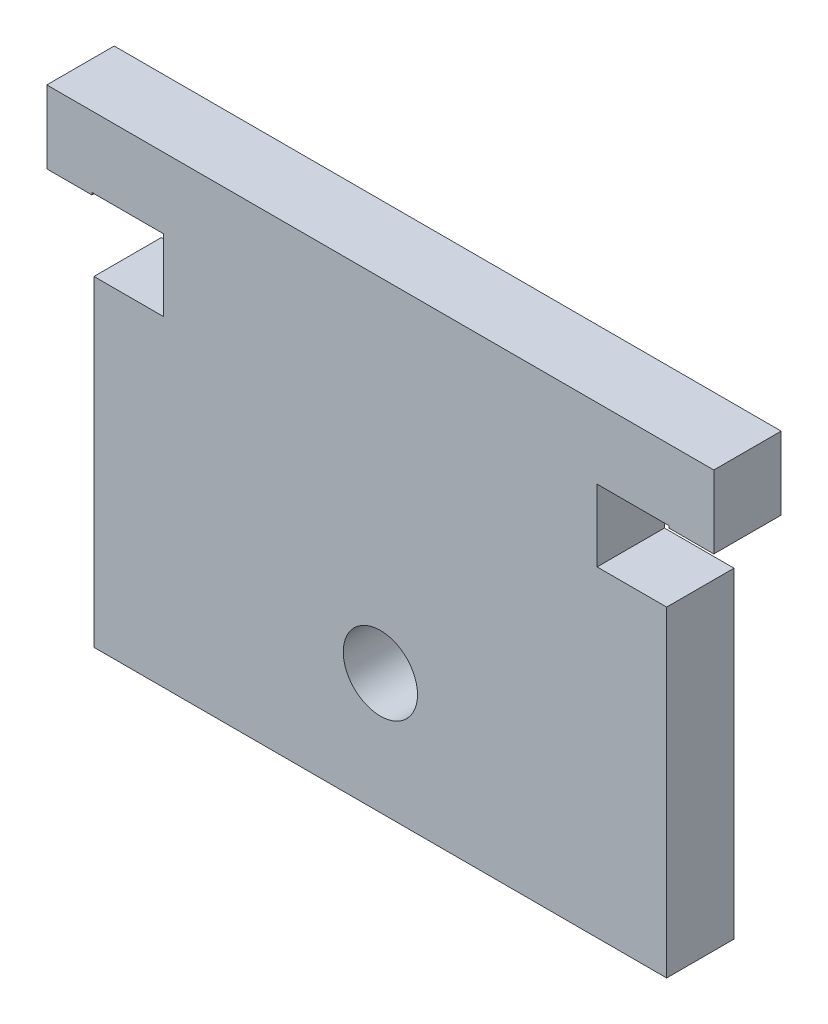
SolidWorks part; units mm, degrees
material "AISI 4130 Steel, annealed at 865C"
ref_plane "X-Y Datum" through (0, 0, 0) normal (0, 0, 1) x (1, 0, 0)
ref_plane "X-Z Datum" through (0, 0, 0) normal (0, 1, 0) x (1, 0, 0)
ref_plane "Y-Z Datum" through (0, 0, 0) normal (1, 0, 0) x (0, 0, -1)
sketch "Sketch1" plane through (0, 0, 0) normal (0, 0, 1) x (1, 0, 0)
  line L1 (-42.8625, -25.4) -> (42.8625, -25.4)
  line L2 (-42.8625, -25.4) -> (-42.8625, 25.4)
  line L3 (-42.8625, 25.4) -> (42.8625, 25.4)
  line L4 (42.8625, -25.4) -> (42.8625, 25.4)
  line L5 (-42.8625, -25.4) -> (42.8625, 25.4) construction
  line L6 (-42.8625, 25.4) -> (42.8625, -25.4) construction
  point P0 (0, 0)
  dimension "D1" = 85.725
  dimension "D2" = 50.8
extrude "Boss-Extrude1" add sketch "Sketch1" along normal blind 6.35
sketch "Sketch2" plane through (0, 0, 6.35) normal (0, 0, 1) x (1, 0, 0)
  line L1 (-42.8625, -25.4) -> (-26.9875, -25.4)
  line L2 (-42.8625, -25.4) -> (-42.8625, 17.78)
  line L3 (-42.8625, 17.78) -> (-26.9875, 17.78)
  line L4 (-26.9875, -25.4) -> (-26.9875, 17.78)
  line L5 (42.8625, -25.4) -> (26.9875, -25.4)
  line L6 (42.8625, -25.4) -> (42.8625, 17.78)
  line L7 (42.8625, 17.78) -> (26.9875, 17.78)
  line L8 (26.9875, -25.4) -> (26.9875, 17.78)
  dimension "D1" = 15.875
  dimension "D2" = 43.18
extrude "Cut-Extrude1" cut sketch "Sketch2" against normal blind 6.35
sketch "Sketch3" plane through (0, 25.4, 0) normal (0, 1, 0) x (1, 0, 0)
  line L1 (-42.8625, 0) -> (42.8625, 0)
  line L2 (-42.8625, 0) -> (-42.8625, -6.35)
  line L3 (-42.8625, -6.35) -> (42.8625, -6.35)
  line L4 (42.8625, 0) -> (42.8625, -6.35)
extrude "Cut-Extrude2" cut sketch "Sketch3" against normal blind 0.762
sketch "Sketch5" plane through (-26.9875, 0, 0) normal (-1, 0, 0) x (0, 0, 1)
  line L0 (6.35, -25.4) -> (6.35, 17.78) construction
  line L1 (0, 17.78) -> (6.35, 17.78)
  line L2 (0, 17.78) -> (0, 11.43)
  line L3 (0, 11.43) -> (6.35, 11.43)
  line L4 (6.35, 17.78) -> (6.35, 11.43)
  dimension "D1" = 6.35
extrude "Cut-Extrude3" cut sketch "Sketch5" against normal blind 6.35
mirror "Mirror1" about plane through (0, 0, 0) normal (1, 0, 0) of "Cut-Extrude3"
sketch "Sketch6" plane through (0, 0, 6.35) normal (0, 0, 1) x (1, 0, 0)
  line L12 (26.9875, 11.43) -> (20.6375, 11.43)
  line L13 (20.6375, 11.43) -> (20.6375, 17.78)
  line L14 (20.6375, 17.78) -> (42.8625, 17.78)
  line L15 (42.8625, 17.78) -> (42.8625, 24.638)
  line L16 (42.8625, 24.638) -> (-42.8625, 24.638)
  line L17 (-42.8625, 24.638) -> (-42.8625, 17.78)
  line L18 (-42.8625, 17.78) -> (-20.6375, 17.78)
  line L19 (-20.6375, 17.78) -> (-20.6375, 11.43)
  line L20 (-20.6375, 11.43) -> (-26.9875, 11.43)
  line L21 (-26.9875, 11.43) -> (-26.9875, -25.4)
  line L22 (-26.9875, -25.4) -> (26.9875, -25.4)
  line L23 (26.9875, -25.4) -> (26.9875, 11.43)
  line L24 (26.9875, 11.43) -> (20.6375, 11.43)
  line L25 (20.6375, 11.43) -> (20.6375, 17.78)
  line L26 (20.6375, 17.78) -> (42.8625, 17.78)
  line L27 (42.8625, 17.78) -> (42.8625, 24.638)
  line L28 (42.8625, 24.638) -> (-42.8625, 24.638)
  line L29 (-42.8625, 24.638) -> (-42.8625, 17.78)
  line L30 (-42.8625, 17.78) -> (-20.6375, 17.78)
  line L31 (-20.6375, 17.78) -> (-20.6375, 11.43)
  line L32 (-20.6375, 11.43) -> (-26.9875, 11.43)
  line L33 (-26.9875, 11.43) -> (-26.9875, -25.4)
  line L34 (-26.9875, -25.4) -> (26.9875, -25.4)
  line L35 (26.9875, -25.4) -> (26.9875, 11.43)
  circle A1 centre (0.0059, -7.6663) radius 3.5
  dimension "D2" = 17.7337
  dimension "D1" = 0
sketch "Sketch7" plane through (-42.8625, 0, 0) normal (-1, 0, 0) x (0, 0, 1)
  line L1 (0, 24.638) -> (6.35, 24.638)
  line L2 (0, 24.638) -> (0, 17.78)
  line L3 (0, 17.78) -> (6.35, 17.78)
  line L4 (6.35, 24.638) -> (6.35, 17.78)
extrude "Cut-Extrude5" cut sketch "Sketch7" against normal blind 11.43
mirror "Mirror2" about plane through (0, 0, 0) normal (1, 0, 0) of "Cut-Extrude5"
sketch "Sketch8" plane through (0, -25.4, 0) normal (0, -1, 0) x (1, 0, 0)
  line L7 (-26.9875, 6.35) -> (26.9875, 6.35)
  line L8 (-26.9875, 6.35) -> (-26.9875, 0)
  line L9 (-26.9875, 0) -> (26.9875, 0)
  line L10 (26.9875, 6.35) -> (26.9875, 0)
extrude "Cut-Extrude6" cut sketch "Sketch8" against normal blind 6.35
hole_wizard "M6 Clearance Hole1" positions "Sketch13" profile "Sketch10" hole size "M6" standard "ANSI Metric" end condition through all
sketch "Sketch13" plane through (0, 0, 6.35) normal (0, 0, 1) x (1, 0, 0)
  point P0 (0.0059, -7.6663)
sketch "Sketch10" plane through (0.0059, -7.6663, 6.35) normal (1, 0, 0) x (0, -1, 0)
  line L0 (0, 0) -> (0, 6.35)
  line L1 (0, 6.35) -> (3.5, 6.35)
  line L2 (3.5, 6.35) -> (3.5, 0)
  line L5 (3.5, 0) -> (0, 0)
  line L11 (0, -6.35) -> (0, 107.95) construction
  dimension "Thru Hole Dia." = 7
  dimension "Thru Hole Depth" = 6.35
sketch "Sketch12" plane through (0, 0, 6.35) normal (0, 0, 1) x (1, 0, 0)
  line L0 (-20.4343, 17.9832) -> (-27.1907, 17.9832)
  line L1 (-20.6375, 17.78) -> (-26.9875, 17.78) construction
  line L2 (-20.6375, 17.78) -> (-20.6375, 11.43) construction
  line L3 (-20.6375, 11.43) -> (-26.9875, 11.43) construction
  line L4 (-26.9875, 17.78) -> (-26.9875, 11.43) construction
  line L5 (20.6375, 17.78) -> (26.9875, 17.78) construction
  line L6 (20.6375, 17.78) -> (20.6375, 11.43) construction
  line L7 (20.6375, 11.43) -> (26.9875, 11.43) construction
  line L8 (26.9875, 17.78) -> (26.9875, 11.43) construction
  line L9 (-27.1907, 17.9832) -> (-27.1907, 11.2268)
  line L10 (-20.4343, 11.2268) -> (-27.1907, 11.2268)
  line L11 (-20.4343, 17.9832) -> (-20.4343, 11.2268)
  line L12 (-26.9875, -19.05) -> (26.9875, -19.05)
  line L13 (26.9875, -19.05) -> (26.9875, 11.43)
  line L14 (26.9875, 11.43) -> (20.6375, 11.43)
  line L15 (20.6375, 11.43) -> (20.6375, 17.78)
  line L16 (20.6375, 17.78) -> (31.4325, 17.78)
  line L17 (31.4325, 17.78) -> (31.4325, 24.638)
  line L18 (31.4325, 24.638) -> (-31.4325, 24.638)
  line L19 (-31.4325, 24.638) -> (-31.4325, 17.78)
  line L20 (-31.4325, 17.78) -> (-20.6375, 17.78)
  line L21 (-20.6375, 17.78) -> (-20.6375, 11.43)
  line L22 (-20.6375, 11.43) -> (-26.9875, 11.43)
  line L23 (-26.9875, 11.43) -> (-26.9875, -19.05)
  line L24 (-26.9875, -19.05) -> (26.9875, -19.05) construction
  line L25 (26.9875, -19.05) -> (26.9875, 11.43) construction
  line L26 (26.9875, 11.43) -> (20.6375, 11.43) construction
  line L27 (20.6375, 11.43) -> (20.6375, 17.78) construction
  line L28 (20.6375, 17.78) -> (31.4325, 17.78) construction
  line L29 (31.4325, 17.78) -> (31.4325, 24.638) construction
  line L30 (31.4325, 24.638) -> (-31.4325, 24.638) construction
  line L31 (-31.4325, 24.638) -> (-31.4325, 17.78) construction
  line L32 (-31.4325, 17.78) -> (-20.6375, 17.78) construction
  line L33 (-20.6375, 17.78) -> (-20.6375, 11.43) construction
  line L34 (-20.6375, 11.43) -> (-26.9875, 11.43) construction
  line L35 (-26.9875, 11.43) -> (-26.9875, -19.05) construction
  line L36 (20.4343, 17.9832) -> (20.4343, 11.2268)
  line L37 (20.4343, 11.2268) -> (27.1907, 11.2268)
  line L38 (27.1907, 17.9832) -> (27.1907, 11.2268)
  line L39 (20.4343, 17.9832) -> (27.1907, 17.9832)
  dimension "D1" = 0
  dimension "D2" = 0.2032
extrude "Cut-Extrude7" cut sketch "Sketch12" against normal through all
